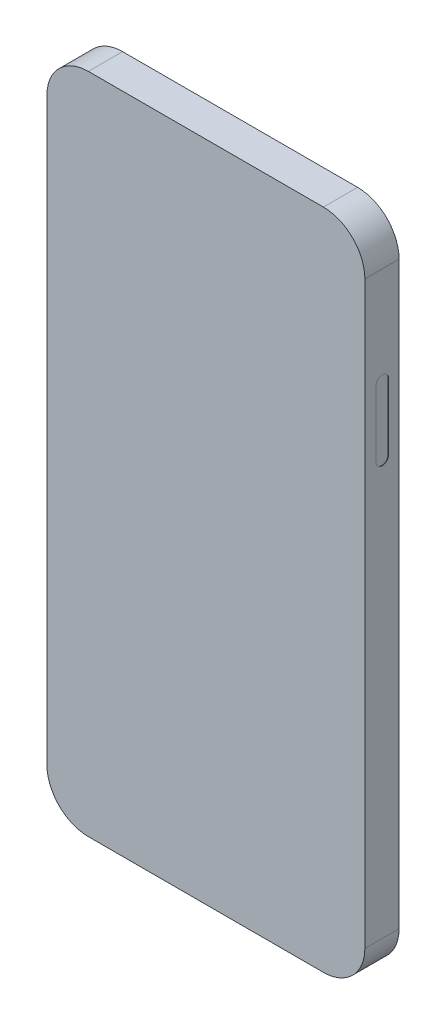
SolidWorks part; units mm, degrees
ref_plane "前视基准面" through (0, 0, 0) normal (0, 0, 1) x (1, 0, 0)
ref_plane "上视基准面" through (0, 0, 0) normal (0, 1, 0) x (1, 0, 0)
ref_plane "右视基准面" through (0, 0, 0) normal (1, 0, 0) x (0, 0, -1)
other "Configuration Table"
sketch "草图1" plane through (0, 0, 0) normal (0, 0, 1) x (1, 0, 0)
  line L1 (-18.0314, 37.3791) -> (38.6686, 37.3791)
  line L2 (-28.0314, 27.3791) -> (-28.0314, -112.5209)
  line L3 (-18.0314, -122.5209) -> (38.6686, -122.5209)
  line L4 (48.6686, 27.3791) -> (48.6686, -112.5209)
  arc A0 (-28.0314, 27.3791) -> (-18.0314, 37.3791) centre (-18.0314, 27.3791) cw
  arc A1 (-18.0314, -122.5209) -> (-28.0314, -112.5209) centre (-18.0314, -112.5209) cw
  arc A2 (48.6686, -112.5209) -> (38.6686, -122.5209) centre (38.6686, -112.5209) cw
  arc A3 (48.6686, 27.3791) -> (38.6686, 37.3791) centre (38.6686, 27.3791) ccw
  point P6 (-28.0314, 37.3791)
  point P9 (-28.0314, -122.5209)
  point P14 (48.6686, 37.3791)
  dimension "D3" = 10
  dimension "D4" = 10
  dimension "D1" = 76.7
  dimension "D2" = 159.9
extrude "凸台-拉伸1" add sketch "草图1" along normal blind 8.25 contours L2 A1 L3 A2 L4 A3 L1 A0
sketch "草图2" plane through (0, -122.5209, 0) normal (0, -1, 0) x (1, 0, 0)
  line L1 (6.4275, 4.7349) -> (14.4275, 4.7349) construction
  line L2 (6.4275, 6.2349) -> (14.4275, 6.2349)
  line L3 (6.4275, 3.2349) -> (14.4275, 3.2349)
  arc A0 (6.4275, 6.2349) -> (6.4275, 3.2349) centre (6.4275, 4.7349) ccw
  arc A1 (14.4275, 3.2349) -> (14.4275, 6.2349) centre (14.4275, 4.7349) ccw
  point P4 (10.4275, 4.7349)
  dimension "D1" = 8
  dimension "D2" = 3
extrude "切除-拉伸1" cut sketch "草图2" against normal blind 5
sketch "草图4" plane through (0, -122.5209, 0) normal (0, -1, 0) x (1, 0, 0)
  circle A0 centre (2, 4.7198) radius 0.5
  circle A1 centre (0, 4.7198) radius 0.5
  circle A2 centre (-2, 4.7198) radius 0.5
  circle A3 centre (-4, 4.7198) radius 0.5
  circle A4 centre (18, 4.7198) radius 0.5172
  circle A5 centre (20, 4.7198) radius 0.5
  circle A6 centre (22, 4.7198) radius 0.5
  circle A7 centre (24, 4.7198) radius 0.5
  circle A8 centre (26, 4.7198) radius 0.5
  circle A9 centre (28, 4.7198) radius 0.5
extrude "切除-拉伸2" cut sketch "草图4" against normal blind 5
sketch "草图5" plane through (48.6686, 0, 0) normal (1, 0, 0) x (0, 0, -1)
  line L0 (-4.0552, 3.7313) -> (-4.0552, -12.2687) construction
  line L1 (-2.5552, 3.7313) -> (-2.5552, -12.2687)
  line L2 (-5.5552, 3.7313) -> (-5.5552, -12.2687)
  arc A0 (-2.5552, 3.7313) -> (-5.5552, 3.7313) centre (-4.0552, 3.7313) ccw
  arc A1 (-5.5552, -12.2687) -> (-2.5552, -12.2687) centre (-4.0552, -12.2687) ccw
  point P2 (-4.0552, -4.2687)
  dimension "D1" = 16
  dimension "D2" = 3
extrude "切除-拉伸3" cut sketch "草图5" against normal blind 0.1
sketch "草图6" plane through (-28.0314, 0, 0) normal (-1, 0, 0) x (0, 0, 1)
  line L0 (4, -11.5) -> (4, -22.5) construction
  line L1 (5.5, -11.5) -> (5.5, -22.5)
  line L2 (2.5, -11.5) -> (2.5, -22.5)
  line L3 (4, 5.5) -> (4, -5.5) construction
  line L4 (5.5, 5.5) -> (5.5, -5.5)
  line L5 (2.5, 5.5) -> (2.5, -5.5)
  arc A0 (5.5, -11.5) -> (2.5, -11.5) centre (4, -11.5) ccw
  arc A1 (2.5, -22.5) -> (5.5, -22.5) centre (4, -22.5) ccw
  circle A2 centre (4.362, 13.88) radius 0.1573
  arc A3 (5.5, 5.5) -> (2.5, 5.5) centre (4, 5.5) ccw
  arc A4 (2.5, -5.5) -> (5.5, -5.5) centre (4, -5.5) ccw
  point P2 (4, -17)
  point P10 (4, 0)
  dimension "D1" = 11
  dimension "D2" = 3
extrude "切除-拉伸4" cut sketch "草图6" against normal blind 0.1
sketch "草图9" plane through (-28.0314, 0, 0) normal (-1, 0, 0) x (0, 0, 1)
  line L0 (4, 18) -> (4, 12) construction
  line L1 (5.5, 18) -> (5.5, 12)
  line L2 (2.5, 18) -> (2.5, 12)
  arc A0 (5.5, 18) -> (2.5, 18) centre (4, 18) ccw
  arc A1 (2.5, 12) -> (5.5, 12) centre (4, 12) ccw
  point P2 (4, 15)
extrude "切除-拉伸5" cut sketch "草图9" against normal blind 0.1
sketch "草图10" plane through (0, 0, 0) normal (0, 0, -1) x (-1, 0, 0)
  line L1 (-31.8301, 25.0336) -> (-7.8301, 25.0336)
  line L2 (-39.8301, 17.0336) -> (-39.8301, -6.9664)
  line L3 (-31.8301, -14.9664) -> (-7.8301, -14.9664)
  line L4 (0.1699, 17.0336) -> (0.1699, -6.9664)
  arc A0 (0.1699, 17.0336) -> (-7.8301, 25.0336) centre (-7.8301, 17.0336) ccw
  arc A1 (-7.8301, -14.9664) -> (0.1699, -6.9664) centre (-7.8301, -6.9664) ccw
  arc A2 (-31.8301, -14.9664) -> (-39.8301, -6.9664) centre (-31.8301, -6.9664) cw
  arc A3 (-39.8301, 17.0336) -> (-31.8301, 25.0336) centre (-31.8301, 17.0336) cw
  point P6 (0.1699, 25.0336)
  point P9 (0.1699, -14.9664)
  point P14 (-39.8301, 25.0336)
  dimension "D3" = 8
  dimension "D1" = 40
  dimension "D2" = 40
extrude "切除-拉伸6" cut sketch "草图10" against normal blind 0.1
sketch "草图11" plane through (-28.0314, 0, 0) normal (-1, 0, 0) x (0, 0, 1)
  line L0 (4, -40) -> (4, -56) construction
  line L1 (5.5, -40) -> (5.5, -56)
  line L2 (2.5, -40) -> (2.5, -56)
  arc A0 (5.5, -40) -> (2.5, -40) centre (4, -40) ccw
  arc A1 (2.5, -56) -> (5.5, -56) centre (4, -56) ccw
  point P2 (4, -48)
extrude "切除-拉伸7" cut sketch "草图11" against normal blind 10
